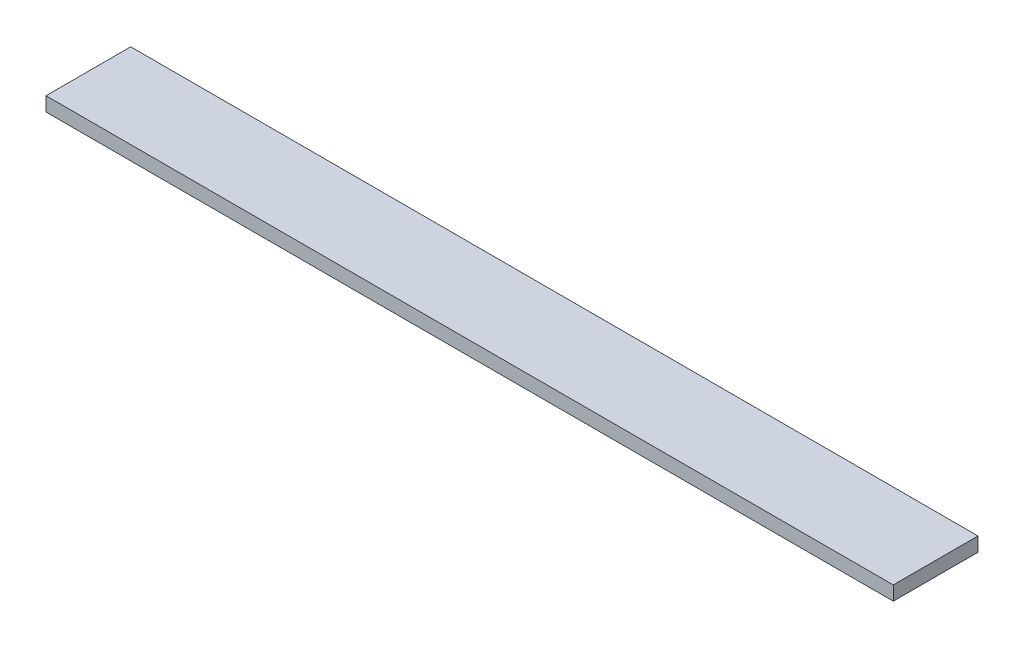
SolidWorks part; units mm, degrees
ref_plane "Front Plane" through (0, 0, 0) normal (0, 0, 1) x (1, 0, 0)
ref_plane "Top Plane" through (0, 0, 0) normal (0, 1, 0) x (1, 0, 0)
ref_plane "Right Plane" through (0, 0, 0) normal (1, 0, 0) x (0, 0, -1)
sketch "Sketch1" plane through (0, 0, 0) normal (0, 1, 0) x (1, 0, 0)
  line L1 (0, 0) -> (600, 0)
  line L2 (0, 0) -> (0, -60)
  line L3 (0, -60) -> (600, -60)
  line L4 (600, 0) -> (600, -60)
  dimension "D1" = 600
  dimension "D2" = 60
extrude "Boss-Extrude1" add sketch "Sketch1" along normal blind 10
